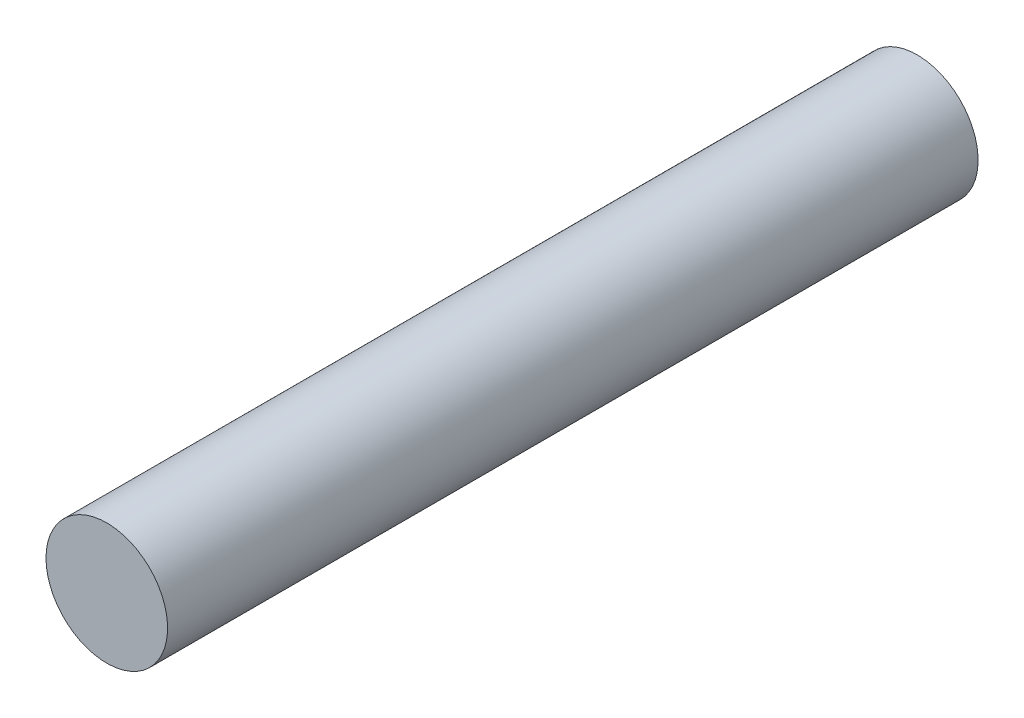
SolidWorks part; units mm, degrees
ref_plane "Plan de face" through (0, 0, 0) normal (0, 0, 1) x (1, 0, 0)
ref_plane "Plan de dessus" through (0, 0, 0) normal (0, 1, 0) x (1, 0, 0)
ref_plane "Plan de droite" through (0, 0, 0) normal (1, 0, 0) x (0, 0, -1)
sketch "Esquisse1" plane through (0, 0, 0) normal (0, 0, 1) x (1, 0, 0)
  circle A0 centre (0, 0) radius 4.5
  dimension "D1" = 9
extrude "Boss.-Extru.1" add sketch "Esquisse1" along normal blind 60
